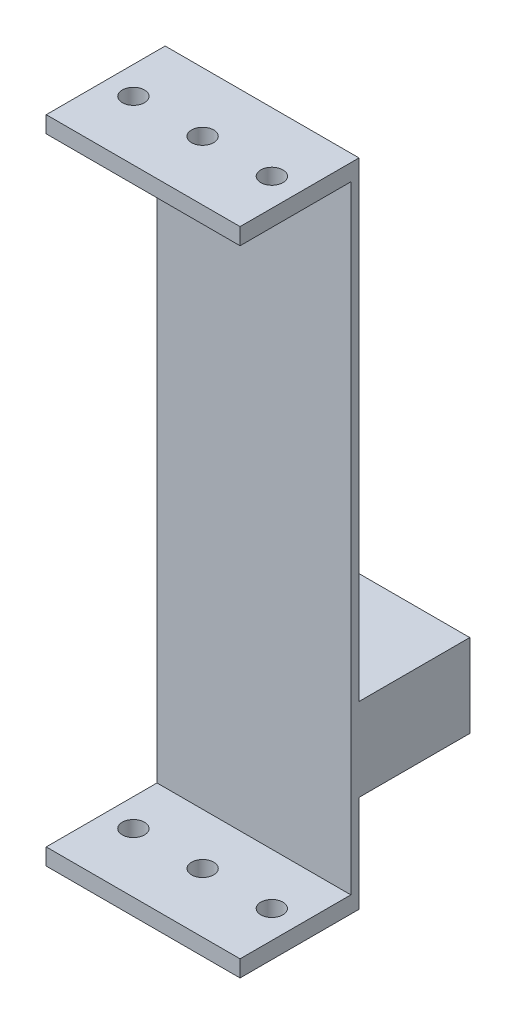
SolidWorks part; units mm, degrees
ref_plane "前视基准面" through (0, 0, 0) normal (0, 0, 1) x (1, 0, 0)
ref_plane "上视基准面" through (0, 0, 0) normal (0, 1, 0) x (1, 0, 0)
ref_plane "右视基准面" through (0, 0, 0) normal (1, 0, 0) x (0, 0, -1)
other "Configuration Table"
sketch "草图1" plane through (0, 0, 0) normal (0, 1, 0) x (1, 0, 0)
  line L0 (0, 0) -> (70, 0)
  line L1 (70, 0) -> (70, 40)
  line L2 (70, 40) -> (0, 40)
  line L3 (0, 40) -> (0, 0)
  dimension "D1" = 70
  dimension "D2" = 40
extrude "凸台-拉伸1" add sketch "草图1" along normal blind 30 contours L3 L0 L1 L2
sketch "草图5" plane through (0, 0, 0) normal (0, 1, 0) x (1, 0, 0)
  line L0 (0, 0) -> (0, -2.9541)
  line L1 (0, -2.9541) -> (70, -2.9541)
  line L2 (70, -2.9541) -> (70, 0)
  line L3 (70, 0) -> (0, 0)
extrude "凸台-拉伸3" add sketch "草图5" against normal blind 35 and the other way blind 200
sketch "草图6" plane through (0, 0, 2.9541) normal (0, 0, 1) x (1, 0, 0)
  line L0 (0, -29) -> (70, -29)
  line L1 (0, 200) -> (0, -35) construction
  line L2 (70, 200) -> (70, -35) construction
  line L3 (70, -29) -> (70, -35)
  line L4 (70, -35) -> (0, -35)
  line L5 (0, -35) -> (0, -29)
  dimension "D1" = 6
extrude "凸台-拉伸4" add sketch "草图6" along normal blind 40
ref_plane "基准面1" through (0, 82.5, 0) normal (0, 1, 0) x (1, 0, 0)
mirror "镜向1" about plane through (0, 82.5, 0) normal (0, 1, 0) of "凸台-拉伸4"
sketch "草图8" plane through (0, 0, 0) normal (0, -1, 0) x (1, 0, 0)
  line L0 (0, -5) -> (70, -5) construction
  line L1 (0, -40) -> (0, 0) construction
  line L2 (70, 0) -> (70, -40) construction
  line L3 (70, 0) -> (0, 0) construction
  line L5 (35, -40) -> (35, 10.2812) construction
  line L6 (70, -40) -> (0, -40) construction
  circle A0 centre (60, -5) radius 1.75
  circle A1 centre (10, -5) radius 1.75
  circle A2 centre (60, -30) radius 1.75
  circle A4 centre (10, -30) radius 1.75
  dimension "D2" = 10
  dimension "D1" = 5
  dimension "D3" = 10
extrude "切除-拉伸1" cut sketch "草图8" against normal blind 6
sketch "草图9" plane through (0, 200, 0) normal (0, 1, 0) x (1, 0, 0)
  line L0 (35, 0) -> (35, -42.9541) construction
  line L1 (70, 0) -> (0, 0) construction
  line L2 (0, -42.9541) -> (70, -42.9541) construction
  line L3 (0, -21.4771) -> (70, -21.4771) construction
  line L4 (0, 0) -> (0, -42.9541) construction
  line L5 (70, -42.9541) -> (70, 0) construction
  circle A0 centre (35, -21.4771) radius 4
  circle A1 centre (60, -21.4771) radius 4
  circle A2 centre (10, -21.4771) radius 4
  dimension "D1" = 10
extrude "切除-拉伸2" cut sketch "草图9" against normal blind 6
mirror "镜向2" about plane through (0, 82.5, 0) normal (0, 1, 0) of "切除-拉伸2"
